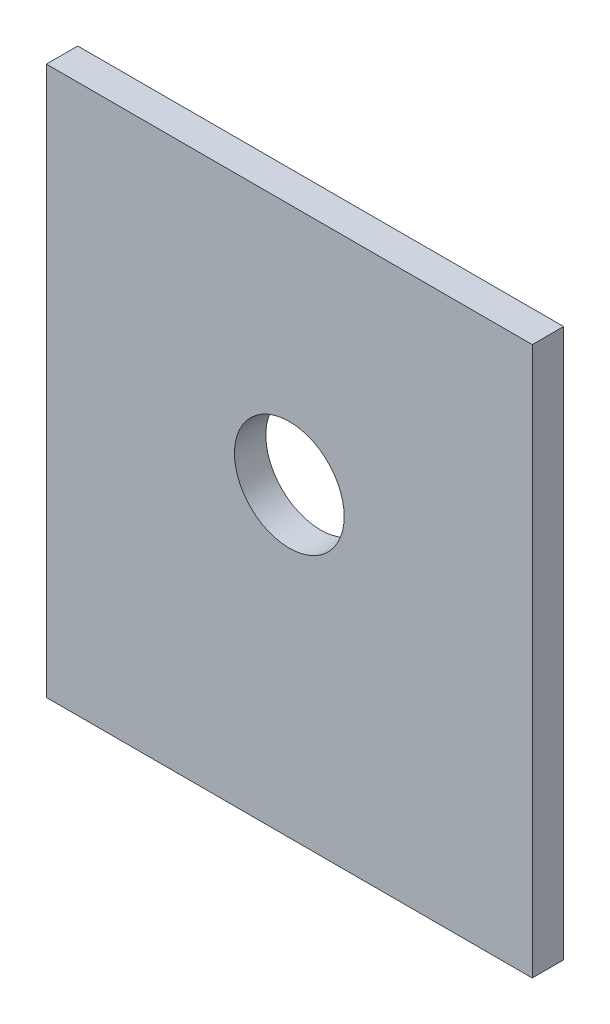
SolidWorks part; units mm, degrees
ref_plane "Front Plane" through (0, 0, 0) normal (0, 0, 1) x (1, 0, 0)
ref_plane "Top Plane" through (0, 0, 0) normal (0, 1, 0) x (1, 0, 0)
ref_plane "Right Plane" through (0, 0, 0) normal (1, 0, 0) x (0, 0, -1)
sketch "Sketch1" plane through (0, 0, 0) normal (0, 0, 1) x (1, 0, 0)
  line L0 (21, 0) -> (21, 42) construction
  line L1 (-10, 52) -> (52, 52)
  line L2 (-10, 52) -> (-10, -18)
  line L3 (-10, -18) -> (52, -18)
  line L4 (52, 52) -> (52, -18)
  line L5 (32, 0) -> (10, 0) construction
  line L6 (42, 42) -> (0, 42) construction
  line L7 (42, 21) -> (0, 21) construction
  line L8 (42, 0) -> (42, 42) construction
  line L9 (0, 42) -> (0, 0) construction
  line L19 (32, -8) -> (10, -8) construction
  circle A0 centre (21, 21) radius 7
  point P16 (21, 52)
  dimension "D4" = 14
  dimension "D1" = 10
  dimension "D2" = 10
  dimension "D3" = 10
extrude "Boss-Extrude1" add sketch "Sketch1" along normal blind 4
